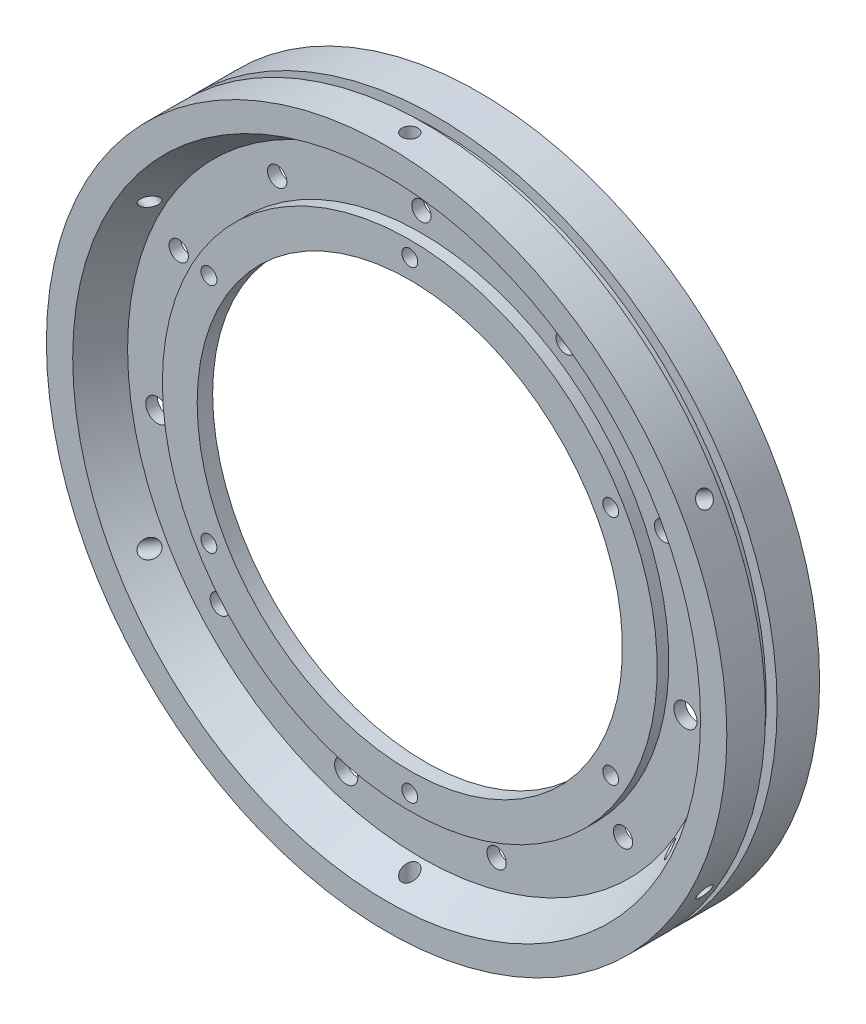
SolidWorks part; units mm, degrees
material "6061-T6 (SS)"
ref_plane "Front Plane" through (0, 0, 0) normal (0, 0, 1) x (1, 0, 0)
ref_plane "Top Plane" through (0, 0, 0) normal (0, 1, 0) x (1, 0, 0)
ref_plane "Right Plane" through (0, 0, 0) normal (1, 0, 0) x (0, 0, -1)
sketch "Sketch1" plane through (0, 0, 0) normal (1, 0, 0) x (0, 0, -1)
  line L0 (0, 0) -> (-48.4987, 0) construction
  line L1 (6, 44) -> (0.5, 44)
  line L2 (0, 55.1576) -> (0, 0) construction
  line L3 (-6, 44) -> (-6, 40.5981)
  line L4 (-6, 40.5981) -> (-1.5, 38)
  line L5 (-1.5, 38) -> (-1.5, 32)
  line L6 (-1.5, 32) -> (-3, 32)
  line L7 (-3, 32) -> (-3, 27.5)
  line L8 (-3, 27.5) -> (-1, 27.5)
  line L9 (0, 30.2475) -> (0, 38)
  line L10 (-1, 44) -> (-6, 44)
  line L11 (-1, 27.5) -> (0, 30.2475)
  line L12 (-1, 44) -> (-1, 42.6)
  line L13 (-1, 42.6) -> (0.5, 42.6)
  line L14 (0.5, 44) -> (0.5, 42.6)
  arc A0 (0, 38) -> (6, 44) centre (6, 38) cw
  dimension "D1" = 6
  dimension "D2" = 6
  dimension "D3" = 55
  dimension "D4" = 88
  dimension "D5" = 30
  dimension "D6" = 76
  dimension "D7" = 64
  dimension "D8" = 1.5
  dimension "D9" = 3
  dimension "D10" = 12
  dimension "D11" = 5
  dimension "D12" = 1.5
  dimension "D13" = 1.4
  dimension "D14" = 1
  dimension "D15" = 20
revolve "Revolve1" add sketch "Sketch1" angle 360 about L0
hole_wizard "M2.5x0.45 Tapped Hole1" positions "Sketch3" profile "Sketch2" tap size "M2.5x0.45" standard "Ansi Metric"
sketch "Sketch3" plane through (0, 0, 3) normal (0, 0, 1) x (1, 0, 0)
  point P0 (0, 30)
  dimension "D1" = 30
sketch "Sketch2" plane through (0, 30, 3) normal (1, 0, 0) x (0, -1, 0)
  line L0 (0, 0) -> (0, 6.9659)
  line L1 (0, 6.9659) -> (1.025, 6.35)
  line L2 (1.025, 6.35) -> (1.025, 0)
  line L5 (1.025, 0) -> (0, 0)
  line L10 (0, 6.9659) -> (-1.025, 6.35) construction
  line L11 (0, -6.35) -> (0, 107.95) construction
  dimension "Tap Drill Dia." = 2.05
  dimension "Tap Drill Depth" = 6.35
  dimension "Drill Angle" = 118
ref_axis "Axis1" through (0, 0, 6.6) along (0, 0, -1)
pattern_circular "CirPattern1" count 6 over 360 about axis through (0, 0, 0) along (0, 0, 1) of "M2.5x0.45 Tapped Hole1"
hole_wizard "Ø2.5 (2.5) Diameter Hole1" positions "Sketch5" profile "Sketch4" hole size "Ø2.5" standard "Ansi Metric"
sketch "Sketch5" plane through (0, 0, 1.5) normal (0, 0, 1) x (1, 0, 0)
  point P0 (0, 34.5)
  dimension "D1" = 34.5
sketch "Sketch4" plane through (0, 34.5, 1.5) normal (1, 0, 0) x (0, -1, 0)
  line L0 (0, 0) -> (0, 23.7511)
  line L1 (0, 23.7511) -> (1.25, 23)
  line L2 (1.25, 23) -> (1.25, 0)
  line L5 (1.25, 0) -> (0, 0)
  line L10 (0, 23.7511) -> (-1.25, 23) construction
  line L11 (0, -6.35) -> (0, 107.95) construction
  dimension "Hole Dia." = 2.5
  dimension "Hole Depth" = 23
  dimension "Drill Angle" = 118
pattern_circular "CirPattern2" count 11 over 360 about axis through (0, 0, 0) along (0, 0, 1) of "Ø2.5 (2.5) Diameter Hole1"
hole_wizard "Ø3.0 (3) Diameter Hole1" positions "Sketch7" profile "Sketch6" hole size "Ø3.0" standard "Ansi Metric"
sketch "Sketch7" plane through (0, 0, 1.5) normal (0, 0, 1) x (1, 0, 0)
  point P0 (-34.1488, -4.9099)
  point P1 (-9.7198, -33.1025)
  point P4 (34.1488, -4.9099)
sketch "Sketch6" plane through (-34.1488, -4.9099, 1.5) normal (1, 0, 0) x (0, -1, 0)
  line L0 (0, 0) -> (0, 23.9013)
  line L1 (0, 23.9013) -> (1.5, 23)
  line L2 (1.5, 23) -> (1.5, 0)
  line L5 (1.5, 0) -> (0, 0)
  line L10 (0, 23.9013) -> (-1.5, 23) construction
  line L11 (0, -6.35) -> (0, 107.95) construction
  dimension "Hole Dia." = 3
  dimension "Hole Depth" = 23
  dimension "Drill Angle" = 118
ref_plane "Plane1" through (0, 44, 0) normal (0, 1, 0) x (-1, 0, 0)
hole_wizard "M2.5x0.45 Tapped Hole2" positions "Sketch9" profile "Sketch8" tap size "M2.5x0.45" standard "Ansi Metric"
sketch "Sketch9" plane through (0, 44, 0) normal (0, 1, 0) x (-1, 0, 0)
  line L0 (0, 6.6) -> (0, -6.6) construction
  line L1 (44, 6) -> (-44, 6) construction
  point P0 (0, 3)
  dimension "D1" = 3
sketch "Sketch8" plane through (0, 44, 3) normal (1, 0, 0) x (0, 0, 1)
  line L0 (0, 0) -> (0, 6.9659)
  line L1 (0, 6.9659) -> (1.025, 6.35)
  line L2 (1.025, 6.35) -> (1.025, 0)
  line L5 (1.025, 0) -> (0, 0)
  line L10 (0, 6.9659) -> (-1.025, 6.35) construction
  line L11 (0, -6.35) -> (0, 107.95) construction
  dimension "Tap Drill Dia." = 2.05
  dimension "Tap Drill Depth" = 6.35
  dimension "Drill Angle" = 118
pattern_circular "CirPattern3" count 6 over 360 about axis through (0, 0, 6.6) along (0, 0, -1) of "M2.5x0.45 Tapped Hole2"
